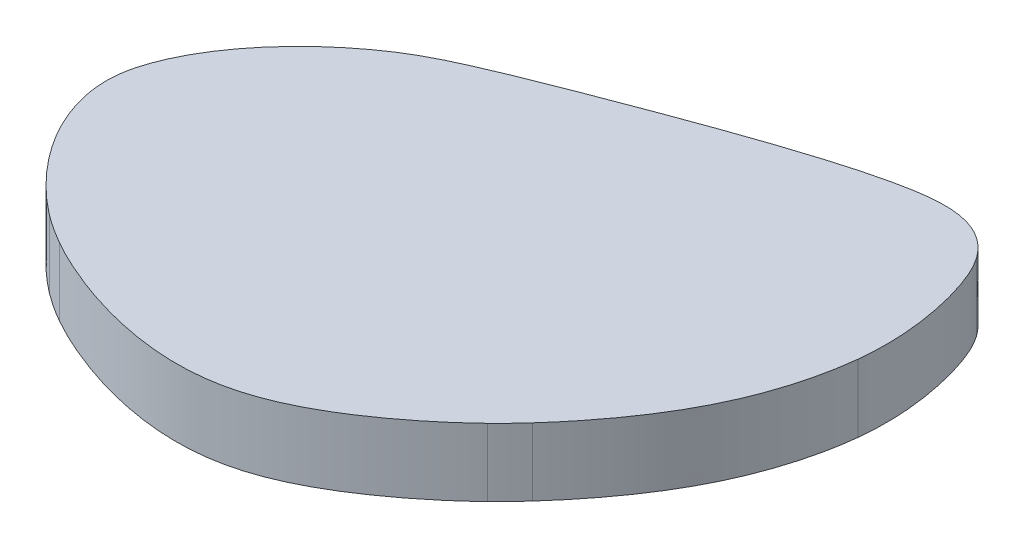
SolidWorks part; units mm, degrees
ref_plane "Спереди" through (0, 0, 0) normal (0, 0, 1) x (1, 0, 0)
ref_plane "Сверху" through (0, 0, 0) normal (0, 1, 0) x (1, 0, 0)
ref_plane "Справа" through (0, 0, 0) normal (1, 0, 0) x (0, 0, -1)
sketch "Sketch1" plane through (0, 0, 0) normal (0, 1, 0) x (1, 0, 0)
  spline S0 degree 3 poles (3.5116, 10.082) (2.6838, 9.8046) (1.8638, 9.5152) (0.2303, 8.9238) (-0.5832, 8.6216) (-2.2064, 8.0084) (-3.0163, 7.6976) (-4.629, 7.0622) (-5.4327, 6.7389) (-6.2179, 6.3897) knots 0 0 0 0 0.25 0.25 0.5 0.5 0.75 0.75 1 1 1 1
  spline S1 degree 3 poles (-6.2179, 6.3897) (-6.7324, 6.1609) (-7.2345, 5.9216) (-8.1835, 5.3955) (-8.6266, 5.1053) (-9.0488, 4.7931) knots 0 0 0 0 0.5 0.5 1 1 1 1
  spline S2 degree 3 poles (-9.0488, 4.7931) (-9.5726, 4.4059) (-10.062, 3.9925) (-10.9769, 3.119) (-11.4033, 2.6569) (-12.1805, 1.6812) (-12.5306, 1.1667) (-12.9801, 0.3515) (-13.1163, 0.0736) (-13.3552, -0.4966) (-13.4585, -0.7888) (-13.5371, -1.0905) knots 0 0 0 0 0.25 0.25 0.5 0.5 0.75 0.75 0.875 0.875 1 1 1 1
  spline S3 degree 3 poles (-13.5371, -1.0905) (-13.6045, -1.3493) (-13.6533, -1.6107) (-13.6986, -2.1384) (-13.6948, -2.4048) (-13.6691, -2.6743) knots 0 0 0 0 0.5 0.5 1 1 1 1
  spline S4 degree 3 poles (-13.6691, -2.6743) (-13.6147, -3.245) (-13.4651, -3.8019) (-13.1323, -4.6252) (-13.0028, -4.8973) (-12.7167, -5.4248) (-12.5593, -5.6818) (-12.0487, -6.4347) (-11.6581, -6.9149) (-10.7901, -7.826) (-10.3222, -8.2521) (-9.8128, -8.6384) knots 0 0 0 0 0.25 0.25 0.375 0.375 0.5 0.5 0.75 0.75 1 1 1 1
  spline S5 degree 3 poles (-9.8128, -8.6384) (-9.4034, -8.9488) (-8.9712, -9.2281) (-8.5219, -9.4839) knots 0 0 0 0 1 1 1 1
  spline S6 degree 3 poles (-8.5219, -9.4839) (-7.8641, -9.8586) (-7.1814, -10.1714) (-5.7864, -10.7217) (-5.0719, -10.9535) (-3.6053, -11.3169) (-2.8495, -11.4476) (-1.7182, -11.5318) (-1.3402, -11.5415) (-0.5823, -11.5173) (-0.1997, -11.4828) (0.9236, -11.3045) (1.6436, -11.0863) (2.6908, -10.6448) (3.0347, -10.4783) (3.7006, -10.1218) (4.0248, -9.9311) (4.9771, -9.3304) (5.5854, -8.892) (6.764, -7.9601) (7.3341, -7.4663) (7.8795, -6.9361) knots 0 0 0 0 0.125 0.125 0.25 0.25 0.375 0.375 0.4375 0.4375 0.5 0.5 0.625 0.625 0.6875 0.6875 0.75 0.75 0.875 0.875 1 1 1 1
  spline S7 degree 3 poles (7.8795, -6.9361) (8.217, -6.608) (8.5425, -6.2681) (8.8589, -5.9192) knots 0 0 0 0 1 1 1 1
  spline S8 degree 3 poles (8.8589, -5.9192) (9.175, -5.5706) (9.4778, -5.2117) (10.0654, -4.4804) (10.3501, -4.1079) (10.8946, -3.3439) (11.1545, -2.9522) (11.6405, -2.1601) (11.8673, -1.7583) (12.2834, -0.9417) (12.4722, -0.5267) (12.8107, 0.316) (12.9614, 0.7459) (13.3509, 2.0343) (13.5279, 2.8825) (13.6174, 3.7143) knots 0 0 0 0 0.125 0.125 0.25 0.25 0.375 0.375 0.5 0.5 0.625 0.625 0.75 0.75 1 1 1 1
  spline S9 degree 3 poles (13.6174, 3.7143) (13.6914, 4.4019) (13.6986, 5.0561) (13.6168, 6.2995) (13.5294, 6.891) (13.3576, 7.7126) (13.2936, 7.9765) (13.1517, 8.485) (13.0737, 8.7297) (12.819, 9.4286) (12.6249, 9.8509) (12.364, 10.2202) knots 0 0 0 0 0.25 0.25 0.5 0.5 0.625 0.625 0.75 0.75 1 1 1 1
  spline S10 degree 3 poles (12.364, 10.2202) (12.223, 10.4199) (12.0642, 10.6003) (11.7023, 10.9221) (11.5012, 11.0646) (11.0334, 11.3043) (10.7639, 11.4023) (10.2991, 11.4956) (10.1325, 11.5177) (9.7827, 11.5405) (9.5984, 11.5415) (9.4045, 11.5326) knots 0 0 0 0 0.25 0.25 0.5 0.5 0.75 0.75 0.875 0.875 1 1 1 1
  spline S11 degree 3 poles (9.4045, 11.5326) (9.1695, 11.5217) (8.9288, 11.4969) (8.4396, 11.4285) (8.1899, 11.3846) (7.441, 11.2355) (6.9426, 11.1135) (5.9492, 10.8469) (5.4576, 10.7028) (4.4805, 10.4014) (3.9951, 10.244) (3.5116, 10.082) knots 0 0 0 0 0.125 0.125 0.25 0.25 0.5 0.5 0.75 0.75 1 1 1 1
extrude "Boss-Extrude1" add sketch "Sketch1" along normal blind 3
